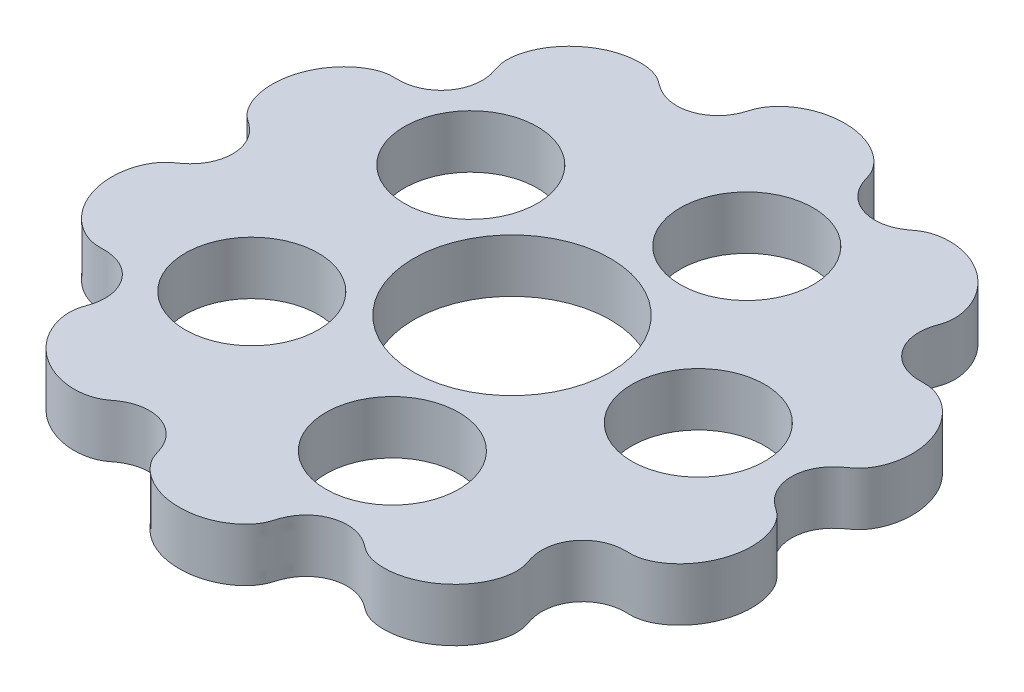
SolidWorks part; units mm, degrees
ref_plane "Front Plane" through (0, 0, 0) normal (0, 0, 1) x (1, 0, 0)
ref_plane "Top Plane" through (0, 0, 0) normal (0, 1, 0) x (1, 0, 0)
ref_plane "Right Plane" through (0, 0, 0) normal (1, 0, 0) x (0, 0, -1)
sketch "Sketch1" plane through (0, 0, 0) normal (0, 1, 0) x (1, 0, 0)
  line L0 (52.5001, 0.0415) -> (52.5, 0)
  spline S0 degree 4 poles (50.5137, 27.6197) (50.9839, 27.5812) (51.8522, 27.4156) (53.4265, 26.845) (55.5206, 25.4783) (57.5342, 23.3814) (59.2047, 20.4519) (60.0271, 17.5454) (60.2034, 14.9243) (59.9788, 12.88) (59.6275, 11.4276) (59.1883, 10.2668) (58.7445, 9.3842) (58.2852, 8.6575) (57.8967, 8.1479) (57.5285, 7.7404) (57.208, 7.4353) (56.9519, 7.2176) (56.636, 6.976) (56.3222, 6.7567) (56.0097, 6.5358) (55.6427, 6.2595) (55.2623, 5.9506) (54.8217, 5.547) (54.3431, 5.0304) (53.8948, 4.4489) (53.5024, 3.829) (53.1698, 3.1757) (52.9427, 2.6012) (52.7935, 2.1219) (52.6991, 1.7471) (52.6422, 1.4822) (52.5946, 1.2148) (52.5565, 0.9474) (52.5279, 0.6739) (52.5088, 0.4201) (52.4999, 0.1167) (52.4991, -0.0504) (52.5043, -0.2752) (52.5136, -0.4749) (52.531, -0.7089) (52.5611, -0.9887) (52.6094, -1.3156) (52.6824, -1.6816) (52.7948, -2.1324) (53.0174, -2.8309) (53.4278, -3.7531) (54.0707, -4.7446) (54.8301, -5.5754) (55.5037, -6.157) (56.0124, -6.539) (56.4108, -6.818) (56.7924, -7.0894) (57.142, -7.3728) (57.5207, -7.7299) (57.9157, -8.1698) (58.4933, -8.9376) (59.0883, -9.9991) (59.6003, -11.3023) (60.0493, -13.197) (60.2144, -15.3932) (59.9369, -17.9726) (59.1239, -20.4456) (58.0615, -22.4161) (56.9372, -23.9185) (55.905, -25.0086) (54.6695, -26.0286) (53.2974, -26.8599) (52.0381, -27.3608) (50.9617, -27.59) (50.2174, -27.6452) (49.7229, -27.6436) (49.2436, -27.6335) (48.779, -27.6384) (48.2213, -27.6667) (47.4128, -27.7584) (46.3618, -27.9976) (45.1066, -28.5075) (43.8309, -29.342) (42.7421, -30.4104) (41.8865, -31.6717) (41.3014, -33.0572) (40.9958, -34.5041) (40.9663, -35.8518) (41.1191, -36.9419) (41.3328, -37.7752) (41.5169, -38.3484) (41.6666, -38.779) (41.8007, -39.1927) (41.9033, -39.5936) (41.9931, -40.0789) (42.0522, -40.6496) (42.0653, -41.3702) (41.996, -42.235) (41.8118, -43.2683) (41.4633, -44.4497) (40.7951, -46.0262) (39.6316, -47.8911) (37.8812, -49.8104) (35.7571, -51.3288) (33.7228, -52.2936) (31.9095, -52.8411) (30.4175, -53.1066) (28.8666, -53.1869) (27.5064, -53.0662) (26.3596, -52.8062) (25.4812, -52.4838) (24.9495, -52.2275) (24.5453, -51.9879) (24.1978, -51.7525) (23.9172, -51.5436) (23.6381, -51.3332) (23.232, -51.041) (22.7473, -50.7202) (21.9663, -50.2822) (20.8507, -49.8374) (19.5115, -49.545) (17.9731, -49.5159) (16.4648, -49.7896) (15.0488, -50.3537) (13.7947, -51.1659) (12.7367, -52.1794) (11.9586, -53.2621) (11.4706, -54.2355) (11.1728, -55.0336) (10.9942, -55.6012) (10.863, -56.033) (10.7199, -56.4397) (10.5576, -56.817) (10.3352, -57.2528) (10.0392, -57.7376) (9.6188, -58.3143) (9.0494, -58.9575) (8.026, -59.9148) (6.4149, -61.014) (4.1854, -61.9905) (1.3392, -62.5603) (-1.5555, -62.5373) (-4.0271, -62.0021) (-6.0205, -61.178) (-7.4336, -60.3182) (-8.3498, -59.6134) (-9.0591, -58.943) (-9.5889, -58.3483) (-10.0398, -57.7416) (-10.3653, -57.2066) (-10.602, -56.7252) (-10.7847, -56.2661) (-10.9036, -55.901) (-11.0089, -55.5537) (-11.134, -55.1628) (-11.2692, -54.775) (-11.524, -54.1353) (-11.9704, -53.2592) (-12.6641, -52.2657) (-13.6882, -51.2531) (-14.8984, -50.4381) (-16.2819, -49.8468) (-17.79, -49.53) (-19.3539, -49.5225) (-20.902, -49.8356) (-22.1148, -50.342) (-22.9585, -50.8486) (-23.5039, -51.2352) (-23.8505, -51.4923) (-24.1373, -51.7091) (-24.4322, -51.9153) (-24.8449, -52.1675) (-25.3219, -52.4127) (-25.9648, -52.6717) (-26.7816, -52.9052) (-27.8082, -53.0938) (-29.0445, -53.179) (-30.4446, -53.106) (-31.9828, -52.8257) (-33.8493, -52.2469) (-35.9581, -51.2161) (-37.8451, -49.8114) (-39.4342, -48.0894) (-40.5175, -46.4752) (-41.2219, -45.0883) (-41.6768, -43.8047) (-41.9333, -42.6668) (-42.0454, -41.7024) (-42.0674, -40.926) (-42.0211, -40.2648) (-41.9322, -39.7238) (-41.8104, -39.2249) (-41.689, -38.8442) (-41.5576, -38.4672) (-41.4084, -38.0119) (-41.2638, -37.5172) (-41.1226, -36.9013) (-41.0183, -36.1616) (-40.9838, -35.3806) (-41.0358, -34.4173) (-41.2507, -33.2654) (-41.725, -31.9746) (-42.561, -30.6268) (-43.6662, -29.4706) (-44.9678, -28.5757) (-46.4068, -27.9666) (-47.6784, -27.6986) (-48.7214, -27.6297) (-49.4554, -27.6377) (-49.8839, -27.6454) (-50.3123, -27.6377) (-50.9842, -27.5865) (-52.0202, -27.3671) (-53.2997, -26.8583) (-54.684, -26.0188) (-55.9292, -24.9892) (-56.989, -23.8601) (-58.1366, -22.3017) (-59.199, -20.2738) (-59.9869, -17.7487) (-60.2196, -15.1335) (-60.0091, -12.9319) (-59.532, -11.1058) (-59.0205, -9.8698) (-58.4445, -8.8705) (-57.9119, -8.1659) (-57.5339, -7.7452) (-57.186, -7.4139) (-56.8826, -7.1604) (-56.5405, -6.9081) (-56.167, -6.6487) (-55.6705, -6.2883) (-54.9929, -5.7308) (-54.2103, -4.9216) (-53.4318, -3.7935) (-52.83, -2.4288) (-52.5002, -0.9669) (-52.4571, 0.5522) (-52.7153, 2.061) (-53.2627, 3.4832) (-54.0035, 4.6556) (-54.7388, 5.4802) (-55.3636, 6.0389) (-55.8227, 6.3989) (-56.1997, 6.6716) (-56.5809, 6.9362) (-56.9524, 7.213) (-57.357, 7.5655) (-57.779, 8.0056) (-58.333, 8.7033) (-58.9309, 9.69) (-59.4684, 10.9205) (-59.881, 12.3939) (-60.1041, 13.8869) (-60.1629, 15.7726) (-59.8944, 18.0319) (-59.2221, 20.2152) (-58.1717, 22.2394) (-57.0556, 23.7771) (-56.0256, 24.8955) (-54.8008, 25.934) (-53.5992, 26.6866) (-52.4791, 27.1881) (-51.5414, 27.4638) (-50.908, 27.5862) (-50.3231, 27.6424) (-49.7934, 27.6455) (-49.1614, 27.6309) (-48.4256, 27.6439) (-47.4521, 27.7432) (-46.2534, 28.0311) (-44.967, 28.579) (-43.6819, 29.4595) (-42.5816, 30.6012) (-41.7415, 31.9406) (-41.2602, 33.2313) (-41.0399, 34.3848) (-40.9839, 35.3498) (-41.0156, 36.1324) (-41.1174, 36.8734) (-41.2569, 37.4904) (-41.4004, 37.9861) (-41.549, 38.442) (-41.6805, 38.8194) (-41.8032, 39.2) (-41.9273, 39.699) (-42.0184, 40.2402) (-42.0669, 40.9021) (-42.0471, 41.6796) (-41.9591, 42.4524) (-41.8098, 43.2156) (-41.553, 44.1531) (-41.1412, 45.2456) (-40.5256, 46.4617) (-39.4424, 48.0795) (-37.854, 49.8036) (-35.9683, 51.2097) (-33.8615, 52.2416) (-31.9987, 52.8217) (-30.4634, 53.1036) (-28.8372, 53.1913) (-27.4076, 53.0564) (-26.2012, 52.7644) (-25.2794, 52.3967) (-24.6778, 52.0804) (-24.2175, 51.7696) (-23.874, 51.5099) (-23.5282, 51.253) (-22.9846, 50.8655) (-22.1441, 50.3567) (-20.9354, 49.8462) (-19.3913, 49.5265) (-17.8293, 49.5261) (-16.3197, 49.835) (-14.9321, 50.4197) (-13.7159, 51.2302) (-12.6861, 52.2396) (-11.9875, 53.2313) (-11.5372, 54.1066) (-11.2802, 54.7459) (-11.1435, 55.1346) (-11.0173, 55.5266) (-10.9116, 55.8747) (-10.7936, 56.2409) (-10.6126, 56.7015) (-10.3777, 57.1843) (-10.0537, 57.7211) (-9.604, 58.33) (-9.0747, 58.927) (-8.3659, 59.5999) (-7.4495, 60.3076) (-6.0356, 61.1707) (-4.0402, 61.9984) (-1.5791, 62.5336) (1.2918, 62.5618) (3.7523, 62.0799) (5.746, 61.3079) (7.1998, 60.4742) (8.1838, 59.7553) (9.0853, 58.9347) (9.773, 58.1413) (10.2664, 57.4013) (10.5906, 56.7517) (10.783, 56.2729) (10.9298, 55.8188) (11.0821, 55.3106) (11.2729, 54.758) (11.5071, 54.1882) (11.7952, 53.6084) (12.2337, 52.8793) (12.8842, 52.0381) (13.7961, 51.1677) (15.0329, 50.3633) (16.4413, 49.7961) (17.9467, 49.5176) (19.4906, 49.5425) (20.9881, 49.8658) (22.167, 50.3685) (23.0025, 50.8774) (23.5419, 51.263) (23.8838, 51.5174) (24.2239, 51.7741) (24.6778, 52.0798) (25.2689, 52.3913) (26.1721, 52.7541) (27.3524, 53.0458) (28.7524, 53.1873) (30.3468, 53.1154) (31.8542, 52.855) (33.6865, 52.3092) (35.7348, 51.3434) (37.8679, 49.8229) (39.6227, 47.9021) (40.7867, 46.0415) (41.4564, 44.4684) (41.8066, 43.2894) (41.9928, 42.2582) (42.0643, 41.3949) (42.0536, 40.6755) (41.9967, 40.1055) (41.9092, 39.6204) (41.8084, 39.2195) (41.676, 38.8059) (41.5263, 38.3761) (41.3414, 37.8045) (41.1252, 36.9734) (40.9684, 35.8858) (40.9919, 34.5404) (41.2901, 33.0941) (41.8697, 31.7015) (42.7272, 30.4257) (43.8268, 29.3427) (45.1246, 28.4959) (46.3067, 28.0217) (47.2768, 27.7899) (48.0092, 27.6897) (48.4792, 27.6507) (48.9504, 27.6345) (49.4215, 27.6363) (49.8923, 27.6467) (50.3633, 27.638) (50.9053, 27.5853) (51.5125, 27.4703) (52.3773, 27.2213) (53.4476, 26.7608) (54.6115, 26.0642) (56.1125, 24.854) (57.6371, 23.1341) (58.9891, 20.8488) (59.9328, 17.9964) (60.2137, 15.4073) (60.0515, 13.2142) (59.6063, 11.3218) (59.0976, 10.0195) (58.506, 8.9581) (57.9317, 8.1896) (57.539, 7.749) (57.1625, 7.3909) (56.8149, 7.1065) (56.4347, 6.8345) (56.0365, 6.5563) (55.5274, 6.176) (54.8528, 5.5976) (54.2148, 4.9051) (53.6468, 4.092) (53.2635, 3.3667) (53.0462, 2.8643) (52.8911, 2.4331) (52.7829, 2.0805) (52.6912, 1.7204) (52.6165, 1.3555) (52.5665, 1.0291) (52.5349, 0.7496) (52.5162, 0.516) (52.5059, 0.3168) (52.4995, 0.0913) (52.4994, -0.0498) (52.5037, -0.2593) (52.5117, -0.4351) (52.5205, -0.5703) (52.5346, -0.7372) (52.5633, -1.0062) (52.6182, -1.3763) (52.7261, -1.8914) (52.9083, -2.5128) (53.1636, -3.1635) (53.5039, -3.8331) (53.9066, -4.4669) (54.3673, -5.0599) (54.8485, -5.5734) (55.3344, -6.0144) (55.8114, -6.3927) (56.2105, -6.6789) (56.5558, -6.9194) (56.8563, -7.1425) (57.1104, -7.3492) (57.439, -7.6488) (57.8233, -8.059) (58.2283, -8.5752) (58.7047, -9.312) (59.1632, -10.2073) (59.5635, -11.2492) (59.8752, -12.434) (60.1105, -13.9192) (60.1782, -15.9789) (59.8062, -18.5974) (58.6629, -21.6162) (56.9432, -24.0677) (55.1186, -25.7376) (53.5134, -26.7273) (52.3156, -27.2564) (51.3998, -27.5063) (50.8196, -27.5938) (50.5276, -27.6185) knots 0 0 0 0 0 0.003711 0.006927 0.013093 0.019514 0.026363 0.033214 0.036638 0.040062 0.042505 0.044948 0.046387 0.047827 0.049266 0.049986 0.050706 0.051309 0.051911 0.053117 0.053719 0.054322 0.055527 0.056973 0.058419 0.05986 0.0613 0.062741 0.064183 0.064716 0.06525 0.065783 0.066317 0.06685 0.067384 0.067918 0.068451 0.068823 0.069195 0.069567 0.069939 0.070683 0.071427 0.072155 0.072882 0.074337 0.077196 0.080074 0.082134 0.083164 0.084195 0.08508 0.085965 0.08685 0.087735 0.089174 0.090614 0.094403 0.097279 0.100155 0.105904 0.111655 0.117552 0.1205 0.123448 0.126397 0.129346 0.133079 0.136028 0.137001 0.137974 0.138947 0.13992 0.140776 0.141631 0.143342 0.146321 0.149231 0.152234 0.155269 0.158252 0.161152 0.164002 0.166843 0.168806 0.169787 0.170769 0.171582 0.172396 0.17321 0.174024 0.175466 0.176908 0.178876 0.180844 0.183715 0.186585 0.192323 0.198063 0.204015 0.206991 0.209967 0.212943 0.215919 0.219183 0.220677 0.222171 0.223273 0.223823 0.224374 0.225475 0.226025 0.226576 0.228312 0.230048 0.233064 0.235996 0.239038 0.242085 0.245052 0.247918 0.250729 0.253554 0.255493 0.256462 0.257431 0.258238 0.259046 0.259854 0.260662 0.262088 0.263514 0.265465 0.267416 0.273101 0.278785 0.28447 0.290104 0.295736 0.298553 0.30137 0.303095 0.30482 0.306227 0.307634 0.309039 0.309742 0.310445 0.311522 0.312061 0.312599 0.313677 0.314754 0.317479 0.320324 0.323167 0.326029 0.328899 0.332099 0.335219 0.338253 0.341251 0.342384 0.34295 0.343516 0.344649 0.345215 0.345781 0.347323 0.348865 0.350662 0.352459 0.355528 0.358598 0.361668 0.364738 0.370878 0.376986 0.38004 0.383094 0.386148 0.389202 0.390729 0.392257 0.393783 0.395309 0.395938 0.396567 0.397824 0.398453 0.399082 0.400339 0.401881 0.403423 0.404954 0.406485 0.409464 0.412615 0.415708 0.418884 0.421967 0.424963 0.427932 0.429056 0.43018 0.430743 0.431305 0.432429 0.43548 0.439041 0.442082 0.445123 0.448164 0.451204 0.457286 0.46306 0.468832 0.47172 0.474607 0.47788 0.479326 0.480773 0.48155 0.482328 0.483106 0.483883 0.484896 0.485909 0.487935 0.490785 0.493727 0.496638 0.499606 0.502511 0.505617 0.508611 0.511524 0.513364 0.514284 0.515204 0.516115 0.517026 0.517938 0.518849 0.520335 0.521821 0.52494 0.527905 0.530869 0.533833 0.536797 0.542726 0.548698 0.551683 0.554667 0.557654 0.56064 0.564291 0.565785 0.56728 0.568321 0.569363 0.570405 0.571447 0.5733 0.575153 0.578095 0.581117 0.58424 0.587334 0.590492 0.593476 0.595011 0.596546 0.59809 0.599633 0.600892 0.601521 0.602151 0.603409 0.604039 0.604668 0.606196 0.607725 0.609254 0.610783 0.612313 0.613842 0.6169 0.619959 0.623017 0.629134 0.635265 0.63833 0.641395 0.644459 0.647524 0.651113 0.652653 0.654193 0.655323 0.656453 0.657019 0.657584 0.658714 0.661709 0.664737 0.667852 0.671048 0.673919 0.676788 0.679636 0.682487 0.685207 0.686288 0.687369 0.687909 0.68845 0.68953 0.690234 0.690937 0.692343 0.693753 0.695162 0.696889 0.698617 0.701438 0.70426 0.7099 0.715542 0.721126 0.72671 0.729502 0.732295 0.73429 0.736286 0.739084 0.740539 0.741266 0.741994 0.743144 0.744294 0.745444 0.746594 0.74799 0.749386 0.752135 0.754942 0.757861 0.760934 0.764011 0.766914 0.769939 0.772922 0.774041 0.7746 0.775159 0.776277 0.777396 0.778902 0.780409 0.783927 0.786931 0.789935 0.792938 0.795942 0.801949 0.80768 0.813409 0.816275 0.819141 0.821107 0.823072 0.824512 0.825951 0.826764 0.827577 0.82839 0.829203 0.830182 0.831161 0.833118 0.835958 0.838802 0.841696 0.844677 0.847761 0.850824 0.853764 0.856799 0.857727 0.858655 0.859582 0.86051 0.861437 0.862364 0.86329 0.864217 0.86572 0.867222 0.870363 0.873362 0.876361 0.882358 0.888357 0.894099 0.89984 0.902711 0.905583 0.909366 0.910804 0.912242 0.913125 0.914008 0.914891 0.915774 0.916804 0.917834 0.919893 0.922762 0.924189 0.925616 0.926343 0.927069 0.927795 0.928521 0.929264 0.930008 0.930379 0.930751 0.931123 0.931494 0.932028 0.932295 0.932562 0.932829 0.933096 0.93363 0.934697 0.935765 0.937242 0.938718 0.940194 0.941669 0.943146 0.944622 0.945727 0.946831 0.947936 0.948488 0.949041 0.949777 0.950514 0.951987 0.953461 0.954935 0.957413 0.959892 0.962228 0.964563 0.969234 0.976064 0.982895 0.989723 0.992556 0.995389 0.997695 1 1 1 1 1 construction
  spline S1 degree 4 poles (52.5, 0) (52.5, -0.0408) (52.5008, -0.1231) (52.5043, -0.2752) (52.5136, -0.4749) (52.531, -0.7089) (52.5611, -0.9887) (52.6094, -1.3156) (52.6824, -1.6816) (52.7948, -2.1324) (53.0174, -2.8309) (53.4278, -3.7531) (54.0707, -4.7446) (54.8301, -5.5754) (55.5037, -6.157) (56.0124, -6.539) (56.4108, -6.818) (56.7924, -7.0894) (57.142, -7.3728) (57.5207, -7.7299) (57.9157, -8.1698) (58.4933, -8.9376) (59.0883, -9.9991) (59.6003, -11.3023) (60.0493, -13.197) (60.2144, -15.3932) (59.9369, -17.9726) (59.1239, -20.4456) (58.0615, -22.4161) (56.9372, -23.9185) (55.905, -25.0086) (54.6695, -26.0286) (53.2974, -26.8599) (52.0381, -27.3608) (50.9617, -27.59) (50.2174, -27.6452) (49.7229, -27.6436) (49.2436, -27.6335) (48.779, -27.6384) (48.2213, -27.6667) (47.4128, -27.7584) (46.3618, -27.9976) (45.1066, -28.5075) (43.8309, -29.342) (42.7421, -30.4104) (41.8865, -31.6717) (41.3014, -33.0572) (40.9958, -34.5041) (40.9663, -35.8518) (41.1191, -36.9419) (41.3328, -37.7752) (41.5169, -38.3484) (41.6666, -38.779) (41.8007, -39.1927) (41.9033, -39.5936) (41.9931, -40.0789) (42.0522, -40.6496) (42.0653, -41.3702) (41.996, -42.235) (41.8118, -43.2683) (41.4633, -44.4497) (40.7951, -46.0262) (39.6316, -47.8911) (37.8812, -49.8104) (35.7571, -51.3288) (33.7228, -52.2936) (31.9095, -52.8411) (30.4175, -53.1066) (28.8666, -53.1869) (27.5064, -53.0662) (26.3596, -52.8062) (25.4812, -52.4838) (24.9495, -52.2275) (24.5453, -51.9879) (24.1978, -51.7525) (23.9172, -51.5436) (23.6381, -51.3332) (23.232, -51.041) (22.7473, -50.7202) (21.9663, -50.2822) (20.8507, -49.8374) (19.5115, -49.545) (17.9731, -49.5159) (16.4648, -49.7896) (15.0488, -50.3537) (13.7947, -51.1659) (12.7367, -52.1794) (11.9586, -53.2621) (11.4706, -54.2355) (11.1728, -55.0336) (10.9942, -55.6012) (10.863, -56.033) (10.7199, -56.4397) (10.5576, -56.817) (10.3352, -57.2528) (10.0392, -57.7376) (9.6188, -58.3143) (9.0494, -58.9575) (8.026, -59.9148) (6.4149, -61.014) (4.1854, -61.9905) (1.3392, -62.5603) (-1.5555, -62.5373) (-4.0271, -62.0021) (-6.0205, -61.178) (-7.4336, -60.3182) (-8.3498, -59.6134) (-9.0591, -58.943) (-9.5889, -58.3483) (-10.0398, -57.7416) (-10.3653, -57.2066) (-10.602, -56.7252) (-10.7847, -56.2661) (-10.9036, -55.901) (-11.0089, -55.5537) (-11.134, -55.1628) (-11.2692, -54.775) (-11.524, -54.1353) (-11.9704, -53.2592) (-12.6641, -52.2657) (-13.6882, -51.2531) (-14.8984, -50.4381) (-16.2819, -49.8468) (-17.79, -49.53) (-19.3539, -49.5225) (-20.902, -49.8356) (-22.1148, -50.342) (-22.9585, -50.8486) (-23.5039, -51.2352) (-23.8505, -51.4923) (-24.1373, -51.7091) (-24.4322, -51.9153) (-24.8449, -52.1675) (-25.3219, -52.4127) (-25.9648, -52.6717) (-26.7816, -52.9052) (-27.8082, -53.0938) (-29.0445, -53.179) (-30.4446, -53.106) (-31.9828, -52.8257) (-33.8493, -52.2469) (-35.9581, -51.2161) (-37.8451, -49.8114) (-39.4342, -48.0894) (-40.5175, -46.4752) (-41.2219, -45.0883) (-41.6768, -43.8047) (-41.9333, -42.6668) (-42.0454, -41.7024) (-42.0674, -40.926) (-42.0211, -40.2648) (-41.9322, -39.7238) (-41.8104, -39.2249) (-41.689, -38.8442) (-41.5576, -38.4672) (-41.4084, -38.0119) (-41.2638, -37.5172) (-41.1226, -36.9013) (-41.0183, -36.1616) (-40.9838, -35.3806) (-41.0358, -34.4173) (-41.2507, -33.2654) (-41.725, -31.9746) (-42.561, -30.6268) (-43.6662, -29.4706) (-44.9678, -28.5757) (-46.4068, -27.9666) (-47.6784, -27.6986) (-48.7214, -27.6297) (-49.4554, -27.6377) (-49.8839, -27.6454) (-50.3123, -27.6377) (-50.9842, -27.5865) (-52.0202, -27.3671) (-53.2997, -26.8583) (-54.684, -26.0188) (-55.9292, -24.9892) (-56.989, -23.8601) (-58.1366, -22.3017) (-59.199, -20.2738) (-59.9869, -17.7487) (-60.2196, -15.1335) (-60.0091, -12.9319) (-59.532, -11.1058) (-59.0205, -9.8698) (-58.4445, -8.8705) (-57.9119, -8.1659) (-57.5339, -7.7452) (-57.186, -7.4139) (-56.8826, -7.1604) (-56.5405, -6.9081) (-56.167, -6.6487) (-55.6705, -6.2883) (-54.9929, -5.7308) (-54.2103, -4.9216) (-53.4318, -3.7935) (-52.83, -2.4288) (-52.5002, -0.9669) (-52.4571, 0.5522) (-52.7153, 2.061) (-53.2627, 3.4832) (-54.0035, 4.6556) (-54.7388, 5.4802) (-55.3636, 6.0389) (-55.8227, 6.3989) (-56.1997, 6.6716) (-56.5809, 6.9362) (-56.9524, 7.213) (-57.357, 7.5655) (-57.779, 8.0056) (-58.333, 8.7033) (-58.9309, 9.69) (-59.4684, 10.9205) (-59.881, 12.3939) (-60.1041, 13.8869) (-60.1629, 15.7726) (-59.8944, 18.0319) (-59.2221, 20.2152) (-58.1717, 22.2394) (-57.0556, 23.7771) (-56.0256, 24.8955) (-54.8008, 25.934) (-53.5992, 26.6866) (-52.4791, 27.1881) (-51.5414, 27.4638) (-50.908, 27.5862) (-50.3231, 27.6424) (-49.7934, 27.6455) (-49.1614, 27.6309) (-48.4256, 27.6439) (-47.4521, 27.7432) (-46.2534, 28.0311) (-44.967, 28.579) (-43.6819, 29.4595) (-42.5816, 30.6012) (-41.7415, 31.9406) (-41.2602, 33.2313) (-41.0399, 34.3848) (-40.9839, 35.3498) (-41.0156, 36.1324) (-41.1174, 36.8734) (-41.2569, 37.4904) (-41.4004, 37.9861) (-41.549, 38.442) (-41.6805, 38.8194) (-41.8032, 39.2) (-41.9273, 39.699) (-42.0184, 40.2402) (-42.0669, 40.9021) (-42.0471, 41.6796) (-41.9591, 42.4524) (-41.8098, 43.2156) (-41.553, 44.1531) (-41.1412, 45.2456) (-40.5256, 46.4617) (-39.4424, 48.0795) (-37.854, 49.8036) (-35.9683, 51.2097) (-33.8615, 52.2416) (-31.9987, 52.8217) (-30.4634, 53.1036) (-28.8372, 53.1913) (-27.4076, 53.0564) (-26.2012, 52.7644) (-25.2794, 52.3967) (-24.6778, 52.0804) (-24.2175, 51.7696) (-23.874, 51.5099) (-23.5282, 51.253) (-22.9846, 50.8655) (-22.1441, 50.3567) (-20.9354, 49.8462) (-19.3913, 49.5265) (-17.8293, 49.5261) (-16.3197, 49.835) (-14.9321, 50.4197) (-13.7159, 51.2302) (-12.6861, 52.2396) (-11.9875, 53.2313) (-11.5372, 54.1066) (-11.2802, 54.7459) (-11.1435, 55.1346) (-11.0173, 55.5266) (-10.9116, 55.8747) (-10.7936, 56.2409) (-10.6126, 56.7015) (-10.3777, 57.1843) (-10.0537, 57.7211) (-9.604, 58.33) (-9.0747, 58.927) (-8.3659, 59.5999) (-7.4495, 60.3076) (-6.0356, 61.1707) (-4.0402, 61.9984) (-1.5791, 62.5336) (1.2918, 62.5618) (3.7523, 62.0799) (5.746, 61.3079) (7.1998, 60.4742) (8.1838, 59.7553) (9.0853, 58.9347) (9.773, 58.1413) (10.2664, 57.4013) (10.5906, 56.7517) (10.783, 56.2729) (10.9298, 55.8188) (11.0821, 55.3106) (11.2729, 54.758) (11.5071, 54.1882) (11.7952, 53.6084) (12.2337, 52.8793) (12.8842, 52.0381) (13.7961, 51.1677) (15.0329, 50.3633) (16.4413, 49.7961) (17.9467, 49.5176) (19.4906, 49.5425) (20.9881, 49.8658) (22.167, 50.3685) (23.0025, 50.8774) (23.5419, 51.263) (23.8838, 51.5174) (24.2239, 51.7741) (24.6778, 52.0798) (25.2689, 52.3913) (26.1721, 52.7541) (27.3524, 53.0458) (28.7524, 53.1873) (30.3468, 53.1154) (31.8542, 52.855) (33.6865, 52.3092) (35.7348, 51.3434) (37.8679, 49.8229) (39.6227, 47.9021) (40.7867, 46.0415) (41.4564, 44.4684) (41.8066, 43.2894) (41.9928, 42.2582) (42.0643, 41.3949) (42.0536, 40.6755) (41.9967, 40.1055) (41.9092, 39.6204) (41.8084, 39.2195) (41.676, 38.8059) (41.5263, 38.3761) (41.3414, 37.8045) (41.1252, 36.9734) (40.9684, 35.8858) (40.9919, 34.5404) (41.2901, 33.0941) (41.8697, 31.7015) (42.7272, 30.4257) (43.8268, 29.3427) (45.1246, 28.4959) (46.3067, 28.0217) (47.2768, 27.7899) (48.0092, 27.6897) (48.4792, 27.6507) (48.9504, 27.6345) (49.4215, 27.6363) (49.8923, 27.6467) (50.3633, 27.638) (50.9053, 27.5853) (51.5125, 27.4703) (52.3773, 27.2213) (53.4476, 26.7608) (54.6115, 26.0642) (56.1125, 24.854) (57.6371, 23.1341) (58.9891, 20.8488) (59.9328, 17.9964) (60.2137, 15.4073) (60.0515, 13.2142) (59.6063, 11.3218) (59.0976, 10.0195) (58.506, 8.9581) (57.9317, 8.1896) (57.539, 7.749) (57.1625, 7.3909) (56.8149, 7.1065) (56.4347, 6.8345) (56.0365, 6.5563) (55.5274, 6.176) (54.8528, 5.5976) (54.2148, 4.9051) (53.6468, 4.092) (53.2635, 3.3667) (53.0462, 2.8643) (52.8911, 2.4331) (52.7829, 2.0805) (52.6912, 1.7204) (52.6165, 1.3555) (52.5665, 1.0291) (52.5349, 0.7496) (52.5162, 0.516) (52.5059, 0.3168) (52.5015, 0.1643) (52.5003, 0.0822) (52.5001, 0.0415) knots 0.068451 0.068451 0.068451 0.068451 0.068451 0.068823 0.069195 0.069567 0.069939 0.070683 0.071427 0.072155 0.072882 0.074337 0.077196 0.080074 0.082134 0.083164 0.084195 0.08508 0.085965 0.08685 0.087735 0.089174 0.090614 0.094403 0.097279 0.100155 0.105904 0.111655 0.117552 0.1205 0.123448 0.126397 0.129346 0.133079 0.136028 0.137001 0.137974 0.138947 0.13992 0.140776 0.141631 0.143342 0.146321 0.149231 0.152234 0.155269 0.158252 0.161152 0.164002 0.166843 0.168806 0.169787 0.170769 0.171582 0.172396 0.17321 0.174024 0.175466 0.176908 0.178876 0.180844 0.183715 0.186585 0.192323 0.198063 0.204015 0.206991 0.209967 0.212943 0.215919 0.219183 0.220677 0.222171 0.223273 0.223823 0.224374 0.225475 0.226025 0.226576 0.228312 0.230048 0.233064 0.235996 0.239038 0.242085 0.245052 0.247918 0.250729 0.253554 0.255493 0.256462 0.257431 0.258238 0.259046 0.259854 0.260662 0.262088 0.263514 0.265465 0.267416 0.273101 0.278785 0.28447 0.290104 0.295736 0.298553 0.30137 0.303095 0.30482 0.306227 0.307634 0.309039 0.309742 0.310445 0.311522 0.312061 0.312599 0.313677 0.314754 0.317479 0.320324 0.323167 0.326029 0.328899 0.332099 0.335219 0.338253 0.341251 0.342384 0.34295 0.343516 0.344649 0.345215 0.345781 0.347323 0.348865 0.350662 0.352459 0.355528 0.358598 0.361668 0.364738 0.370878 0.376986 0.38004 0.383094 0.386148 0.389202 0.390729 0.392257 0.393783 0.395309 0.395938 0.396567 0.397824 0.398453 0.399082 0.400339 0.401881 0.403423 0.404954 0.406485 0.409464 0.412615 0.415708 0.418884 0.421967 0.424963 0.427932 0.429056 0.43018 0.430743 0.431305 0.432429 0.43548 0.439041 0.442082 0.445123 0.448164 0.451204 0.457286 0.46306 0.468832 0.47172 0.474607 0.47788 0.479326 0.480773 0.48155 0.482328 0.483106 0.483883 0.484896 0.485909 0.487935 0.490785 0.493727 0.496638 0.499606 0.502511 0.505617 0.508611 0.511524 0.513364 0.514284 0.515204 0.516115 0.517026 0.517938 0.518849 0.520335 0.521821 0.52494 0.527905 0.530869 0.533833 0.536797 0.542726 0.548698 0.551683 0.554667 0.557654 0.56064 0.564291 0.565785 0.56728 0.568321 0.569363 0.570405 0.571447 0.5733 0.575153 0.578095 0.581117 0.58424 0.587334 0.590492 0.593476 0.595011 0.596546 0.59809 0.599633 0.600892 0.601521 0.602151 0.603409 0.604039 0.604668 0.606196 0.607725 0.609254 0.610783 0.612313 0.613842 0.6169 0.619959 0.623017 0.629134 0.635265 0.63833 0.641395 0.644459 0.647524 0.651113 0.652653 0.654193 0.655323 0.656453 0.657019 0.657584 0.658714 0.661709 0.664737 0.667852 0.671048 0.673919 0.676788 0.679636 0.682487 0.685207 0.686288 0.687369 0.687909 0.68845 0.68953 0.690234 0.690937 0.692343 0.693753 0.695162 0.696889 0.698617 0.701438 0.70426 0.7099 0.715542 0.721126 0.72671 0.729502 0.732295 0.73429 0.736286 0.739084 0.740539 0.741266 0.741994 0.743144 0.744294 0.745444 0.746594 0.74799 0.749386 0.752135 0.754942 0.757861 0.760934 0.764011 0.766914 0.769939 0.772922 0.774041 0.7746 0.775159 0.776277 0.777396 0.778902 0.780409 0.783927 0.786931 0.789935 0.792938 0.795942 0.801949 0.80768 0.813409 0.816275 0.819141 0.821107 0.823072 0.824512 0.825951 0.826764 0.827577 0.82839 0.829203 0.830182 0.831161 0.833118 0.835958 0.838802 0.841696 0.844677 0.847761 0.850824 0.853764 0.856799 0.857727 0.858655 0.859582 0.86051 0.861437 0.862364 0.86329 0.864217 0.86572 0.867222 0.870363 0.873362 0.876361 0.882358 0.888357 0.894099 0.89984 0.902711 0.905583 0.909366 0.910804 0.912242 0.913125 0.914008 0.914891 0.915774 0.916804 0.917834 0.919893 0.922762 0.924189 0.925616 0.926343 0.927069 0.927795 0.928521 0.929264 0.930008 0.930379 0.930751 0.931123 0.931494 0.931494 0.931494 0.931494 0.931494
extrude "Boss-Extrude1" add sketch "Sketch1" along normal blind 10
sketch "Sketch2" plane through (0, 10, 0) normal (0, 1, 0) x (1, 0, 0)
  circle A0 centre (0, 0) radius 18.5
  dimension "D1" = 37
extrude "Cut-Extrude1" cut sketch "Sketch2" against normal blind 10
sketch "Sketch3" plane through (0, 10, 0) normal (0, 1, 0) x (1, 0, 0)
  line L0 (10.8156, 33.287) -> (0, 0) construction
  line L2 (0, 0) -> (0, 62.5) construction
  circle A0 centre (10.8156, 33.287) radius 12.5
  circle A1 centre (0, 0) radius 35 construction
  circle A2 centre (35, 0) radius 12.5
  circle A3 centre (10.8156, -33.287) radius 12.5
  circle A4 centre (-28.3156, -20.5725) radius 12.5
  circle A5 centre (-28.3156, 20.5725) radius 12.5
  spline S0 degree 4 poles (52.5001, 0.0415) (52.5003, 0.0822) (52.5015, 0.1643) (52.5059, 0.3168) (52.5162, 0.516) (52.5349, 0.7496) (52.5665, 1.0291) (52.6165, 1.3555) (52.6912, 1.7204) (52.7829, 2.0805) (52.8911, 2.4331) (53.0462, 2.8643) (53.2635, 3.3667) (53.6468, 4.092) (54.2148, 4.9051) (54.8528, 5.5976) (55.5274, 6.176) (56.0365, 6.5563) (56.4347, 6.8345) (56.8149, 7.1065) (57.1625, 7.3909) (57.539, 7.749) (57.9317, 8.1896) (58.506, 8.9581) (59.0976, 10.0195) (59.6063, 11.3218) (60.0515, 13.2142) (60.2137, 15.4073) (59.9328, 17.9964) (58.9891, 20.8488) (57.6371, 23.1341) (56.1125, 24.854) (54.6115, 26.0642) (53.4476, 26.7608) (52.3773, 27.2213) (51.5125, 27.4703) (50.9053, 27.5853) (50.3633, 27.638) (49.8923, 27.6467) (49.4215, 27.6363) (48.9504, 27.6345) (48.4792, 27.6507) (48.0092, 27.6897) (47.2768, 27.7899) (46.3067, 28.0217) (45.1246, 28.4959) (43.8268, 29.3427) (42.7272, 30.4257) (41.8697, 31.7015) (41.2901, 33.0941) (40.9919, 34.5404) (40.9684, 35.8858) (41.1252, 36.9734) (41.3414, 37.8045) (41.5263, 38.3761) (41.676, 38.8059) (41.8084, 39.2195) (41.9092, 39.6204) (41.9967, 40.1055) (42.0536, 40.6755) (42.0643, 41.3949) (41.9928, 42.2582) (41.8066, 43.2894) (41.4564, 44.4684) (40.7867, 46.0415) (39.6227, 47.9021) (37.8679, 49.8229) (35.7348, 51.3434) (33.6865, 52.3092) (31.8542, 52.855) (30.3468, 53.1154) (28.7524, 53.1873) (27.3524, 53.0458) (26.1721, 52.7541) (25.2689, 52.3913) (24.6778, 52.0798) (24.2239, 51.7741) (23.8838, 51.5174) (23.5419, 51.263) (23.0025, 50.8774) (22.167, 50.3685) (20.9881, 49.8658) (19.4906, 49.5425) (17.9467, 49.5176) (16.4413, 49.7961) (15.0329, 50.3633) (13.7961, 51.1677) (12.8842, 52.0381) (12.2337, 52.8793) (11.7952, 53.6084) (11.5071, 54.1882) (11.2729, 54.758) (11.0821, 55.3106) (10.9298, 55.8188) (10.783, 56.2729) (10.5906, 56.7517) (10.2664, 57.4013) (9.773, 58.1413) (9.0853, 58.9347) (8.1838, 59.7553) (7.1998, 60.4742) (5.746, 61.3079) (3.7523, 62.0799) (1.2918, 62.5618) (-1.5791, 62.5336) (-4.0402, 61.9984) (-6.0356, 61.1707) (-7.4495, 60.3076) (-8.3659, 59.5999) (-9.0747, 58.927) (-9.604, 58.33) (-10.0537, 57.7211) (-10.3777, 57.1843) (-10.6126, 56.7015) (-10.7936, 56.2409) (-10.9116, 55.8747) (-11.0173, 55.5266) (-11.1435, 55.1346) (-11.2802, 54.7459) (-11.5372, 54.1066) (-11.9875, 53.2313) (-12.6861, 52.2396) (-13.7159, 51.2302) (-14.9321, 50.4197) (-16.3197, 49.835) (-17.8293, 49.5261) (-19.3913, 49.5265) (-20.9354, 49.8462) (-22.1441, 50.3567) (-22.9846, 50.8655) (-23.5282, 51.253) (-23.874, 51.5099) (-24.2175, 51.7696) (-24.6778, 52.0804) (-25.2794, 52.3967) (-26.2012, 52.7644) (-27.4076, 53.0564) (-28.8372, 53.1913) (-30.4634, 53.1036) (-31.9987, 52.8217) (-33.8615, 52.2416) (-35.9683, 51.2097) (-37.854, 49.8036) (-39.4424, 48.0795) (-40.5256, 46.4617) (-41.1412, 45.2456) (-41.553, 44.1531) (-41.8098, 43.2156) (-41.9591, 42.4524) (-42.0471, 41.6796) (-42.0669, 40.9021) (-42.0184, 40.2402) (-41.9273, 39.699) (-41.8032, 39.2) (-41.6805, 38.8194) (-41.549, 38.442) (-41.4004, 37.9861) (-41.2569, 37.4904) (-41.1174, 36.8734) (-41.0156, 36.1324) (-40.9839, 35.3498) (-41.0399, 34.3848) (-41.2602, 33.2313) (-41.7415, 31.9406) (-42.5816, 30.6012) (-43.6819, 29.4595) (-44.967, 28.579) (-46.2534, 28.0311) (-47.4521, 27.7432) (-48.4256, 27.6439) (-49.1614, 27.6309) (-49.7934, 27.6455) (-50.3231, 27.6424) (-50.908, 27.5862) (-51.5414, 27.4638) (-52.4791, 27.1881) (-53.5992, 26.6866) (-54.8008, 25.934) (-56.0256, 24.8955) (-57.0556, 23.7771) (-58.1717, 22.2394) (-59.2221, 20.2152) (-59.8944, 18.0319) (-60.1629, 15.7726) (-60.1041, 13.8869) (-59.881, 12.3939) (-59.4684, 10.9205) (-58.9309, 9.69) (-58.333, 8.7033) (-57.779, 8.0056) (-57.357, 7.5655) (-56.9524, 7.213) (-56.5809, 6.9362) (-56.1997, 6.6716) (-55.8227, 6.3989) (-55.3636, 6.0389) (-54.7388, 5.4802) (-54.0035, 4.6556) (-53.2627, 3.4832) (-52.7153, 2.061) (-52.4571, 0.5522) (-52.5002, -0.9669) (-52.83, -2.4288) (-53.4318, -3.7935) (-54.2103, -4.9216) (-54.9929, -5.7308) (-55.6705, -6.2883) (-56.167, -6.6487) (-56.5405, -6.9081) (-56.8826, -7.1604) (-57.186, -7.4139) (-57.5339, -7.7452) (-57.9119, -8.1659) (-58.4445, -8.8705) (-59.0205, -9.8698) (-59.532, -11.1058) (-60.0091, -12.9319) (-60.2196, -15.1335) (-59.9869, -17.7487) (-59.199, -20.2738) (-58.1366, -22.3017) (-56.989, -23.8601) (-55.9292, -24.9892) (-54.684, -26.0188) (-53.2997, -26.8583) (-52.0202, -27.3671) (-50.9842, -27.5865) (-50.3123, -27.6377) (-49.8839, -27.6454) (-49.4554, -27.6377) (-48.7214, -27.6297) (-47.6784, -27.6986) (-46.4068, -27.9666) (-44.9678, -28.5757) (-43.6662, -29.4706) (-42.561, -30.6268) (-41.725, -31.9746) (-41.2507, -33.2654) (-41.0358, -34.4173) (-40.9838, -35.3806) (-41.0183, -36.1616) (-41.1226, -36.9013) (-41.2638, -37.5172) (-41.4084, -38.0119) (-41.5576, -38.4672) (-41.689, -38.8442) (-41.8104, -39.2249) (-41.9322, -39.7238) (-42.0211, -40.2648) (-42.0674, -40.926) (-42.0454, -41.7024) (-41.9333, -42.6668) (-41.6768, -43.8047) (-41.2219, -45.0883) (-40.5175, -46.4752) (-39.4342, -48.0894) (-37.8451, -49.8114) (-35.9581, -51.2161) (-33.8493, -52.2469) (-31.9828, -52.8257) (-30.4446, -53.106) (-29.0445, -53.179) (-27.8082, -53.0938) (-26.7816, -52.9052) (-25.9648, -52.6717) (-25.3219, -52.4127) (-24.8449, -52.1675) (-24.4322, -51.9153) (-24.1373, -51.7091) (-23.8505, -51.4923) (-23.5039, -51.2352) (-22.9585, -50.8486) (-22.1148, -50.342) (-20.902, -49.8356) (-19.3539, -49.5225) (-17.79, -49.53) (-16.2819, -49.8468) (-14.8984, -50.4381) (-13.6882, -51.2531) (-12.6641, -52.2657) (-11.9704, -53.2592) (-11.524, -54.1353) (-11.2692, -54.775) (-11.134, -55.1628) (-11.0089, -55.5537) (-10.9036, -55.901) (-10.7847, -56.2661) (-10.602, -56.7252) (-10.3653, -57.2066) (-10.0398, -57.7416) (-9.5889, -58.3483) (-9.0591, -58.943) (-8.3498, -59.6134) (-7.4336, -60.3182) (-6.0205, -61.178) (-4.0271, -62.0021) (-1.5555, -62.5373) (1.3392, -62.5603) (4.1854, -61.9905) (6.4149, -61.014) (8.026, -59.9148) (9.0494, -58.9575) (9.6188, -58.3143) (10.0392, -57.7376) (10.3352, -57.2528) (10.5576, -56.817) (10.7199, -56.4397) (10.863, -56.033) (10.9942, -55.6012) (11.1728, -55.0336) (11.4706, -54.2355) (11.9586, -53.2621) (12.7367, -52.1794) (13.7947, -51.1659) (15.0488, -50.3537) (16.4648, -49.7896) (17.9731, -49.5159) (19.5115, -49.545) (20.8507, -49.8374) (21.9663, -50.2822) (22.7473, -50.7202) (23.232, -51.041) (23.6381, -51.3332) (23.9172, -51.5436) (24.1978, -51.7525) (24.5453, -51.9879) (24.9495, -52.2275) (25.4812, -52.4838) (26.3596, -52.8062) (27.5064, -53.0662) (28.8666, -53.1869) (30.4175, -53.1066) (31.9095, -52.8411) (33.7228, -52.2936) (35.7571, -51.3288) (37.8812, -49.8104) (39.6316, -47.8911) (40.7951, -46.0262) (41.4633, -44.4497) (41.8118, -43.2683) (41.996, -42.235) (42.0653, -41.3702) (42.0522, -40.6496) (41.9931, -40.0789) (41.9033, -39.5936) (41.8007, -39.1927) (41.6666, -38.779) (41.5169, -38.3484) (41.3328, -37.7752) (41.1191, -36.9419) (40.9663, -35.8518) (40.9958, -34.5041) (41.3014, -33.0572) (41.8865, -31.6717) (42.7421, -30.4104) (43.8309, -29.342) (45.1066, -28.5075) (46.3618, -27.9976) (47.4128, -27.7584) (48.2213, -27.6667) (48.779, -27.6384) (49.2436, -27.6335) (49.7229, -27.6436) (50.2174, -27.6452) (50.9617, -27.59) (52.0381, -27.3608) (53.2974, -26.8599) (54.6695, -26.0286) (55.905, -25.0086) (56.9372, -23.9185) (58.0615, -22.4161) (59.1239, -20.4456) (59.9369, -17.9726) (60.2144, -15.3932) (60.0493, -13.197) (59.6003, -11.3023) (59.0883, -9.9991) (58.4933, -8.9376) (57.9157, -8.1698) (57.5207, -7.7299) (57.142, -7.3728) (56.7924, -7.0894) (56.4108, -6.818) (56.0124, -6.539) (55.5037, -6.157) (54.8301, -5.5754) (54.0707, -4.7446) (53.4278, -3.7531) (53.0174, -2.8309) (52.7948, -2.1324) (52.6824, -1.6816) (52.6094, -1.3156) (52.5611, -0.9887) (52.531, -0.7089) (52.5136, -0.4749) (52.5043, -0.2752) (52.5008, -0.1231) (52.5, -0.0408) (52.5, 0) knots 0.068451 0.068451 0.068451 0.068451 0.068451 0.068823 0.069195 0.069566 0.069938 0.070682 0.071425 0.072151 0.072877 0.073603 0.074329 0.075756 0.077184 0.080053 0.082112 0.083142 0.084171 0.085055 0.085938 0.086821 0.087704 0.089142 0.090579 0.094363 0.097234 0.100106 0.105847 0.111589 0.117587 0.123585 0.126584 0.129582 0.132723 0.134226 0.135729 0.136656 0.137582 0.138509 0.139435 0.140363 0.141291 0.142219 0.143147 0.146181 0.149122 0.152185 0.155269 0.158249 0.161144 0.163987 0.166827 0.168785 0.169764 0.170743 0.171556 0.172369 0.173182 0.173995 0.175434 0.176874 0.178839 0.180804 0.18367 0.186536 0.192266 0.197996 0.204004 0.207007 0.21001 0.213015 0.216019 0.219537 0.221043 0.22255 0.223668 0.224787 0.225346 0.225905 0.227024 0.230007 0.233032 0.235935 0.239012 0.242085 0.245003 0.247811 0.250559 0.251955 0.253351 0.254501 0.255652 0.256802 0.257952 0.25868 0.259407 0.260862 0.26366 0.265656 0.267651 0.270443 0.273236 0.27882 0.284404 0.290046 0.295686 0.298507 0.301329 0.303056 0.304784 0.306193 0.307602 0.309009 0.309712 0.310415 0.311496 0.312036 0.312577 0.313658 0.314739 0.317459 0.32031 0.323158 0.326027 0.328898 0.332094 0.335208 0.338237 0.341231 0.342362 0.342927 0.343492 0.344623 0.345753 0.347293 0.348833 0.352422 0.355486 0.358551 0.361616 0.364681 0.370812 0.376929 0.379987 0.383045 0.386104 0.387633 0.389162 0.390692 0.392221 0.393749 0.395278 0.395907 0.396536 0.397795 0.398424 0.399054 0.400312 0.401856 0.4034 0.404934 0.406469 0.409454 0.412611 0.415706 0.418829 0.421851 0.424793 0.426646 0.428499 0.429541 0.430582 0.431624 0.432666 0.43416 0.435655 0.439306 0.442292 0.445278 0.448263 0.451248 0.457219 0.463149 0.466113 0.469077 0.472041 0.475006 0.478125 0.479611 0.481097 0.482008 0.482919 0.483831 0.484742 0.485662 0.486582 0.488422 0.491334 0.494329 0.497434 0.50034 0.503308 0.506219 0.50916 0.512011 0.514037 0.51505 0.516062 0.51684 0.517618 0.518395 0.519173 0.520619 0.522066 0.525339 0.528226 0.531114 0.536886 0.54266 0.548742 0.551782 0.554822 0.557864 0.560905 0.564466 0.567516 0.568641 0.569203 0.569765 0.57089 0.572014 0.574983 0.577978 0.581061 0.584238 0.587331 0.590482 0.593461 0.594992 0.596523 0.598065 0.599607 0.600864 0.601493 0.602121 0.603379 0.604008 0.604636 0.606163 0.607689 0.609216 0.610744 0.613798 0.616852 0.619906 0.622959 0.629068 0.635208 0.638278 0.641348 0.644417 0.647487 0.649284 0.651081 0.652623 0.654165 0.654731 0.655297 0.656429 0.656996 0.657562 0.658694 0.661692 0.664727 0.667847 0.671047 0.673917 0.676779 0.679622 0.682467 0.685192 0.686269 0.687346 0.687885 0.688424 0.689501 0.690204 0.690906 0.692312 0.693719 0.695126 0.696851 0.698576 0.701393 0.70421 0.709842 0.715475 0.72116 0.726844 0.73253 0.734481 0.736432 0.737858 0.739284 0.740092 0.7409 0.741707 0.742515 0.743484 0.744453 0.746391 0.749216 0.752028 0.754894 0.75786 0.760908 0.76395 0.766882 0.769897 0.771634 0.77337 0.77392 0.774471 0.775572 0.776123 0.776673 0.777774 0.779268 0.780763 0.784027 0.787003 0.789979 0.792955 0.795931 0.801883 0.807623 0.813361 0.816231 0.819102 0.82107 0.823038 0.82448 0.825922 0.826736 0.82755 0.828363 0.829177 0.830158 0.83114 0.833102 0.835944 0.838793 0.841694 0.844677 0.847712 0.850714 0.853625 0.856603 0.858314 0.85917 0.860026 0.860999 0.861972 0.862945 0.863918 0.866866 0.8706 0.873549 0.876497 0.879445 0.882393 0.888291 0.894041 0.899791 0.902667 0.905543 0.909332 0.910772 0.912211 0.913096 0.913981 0.914866 0.915751 0.916781 0.917812 0.919872 0.92275 0.925608 0.927063 0.927791 0.928518 0.929262 0.930006 0.930378 0.93075 0.931122 0.931494 0.931494 0.931494 0.931494 0.931494 construction
  point P16 (0, 0)
  dimension "D1" = 70
  dimension "D2" = 25
  dimension "D4" = 18
  dimension "D3" = 5
extrude "Cut-Extrude2" cut sketch "Sketch3" against normal blind 10
